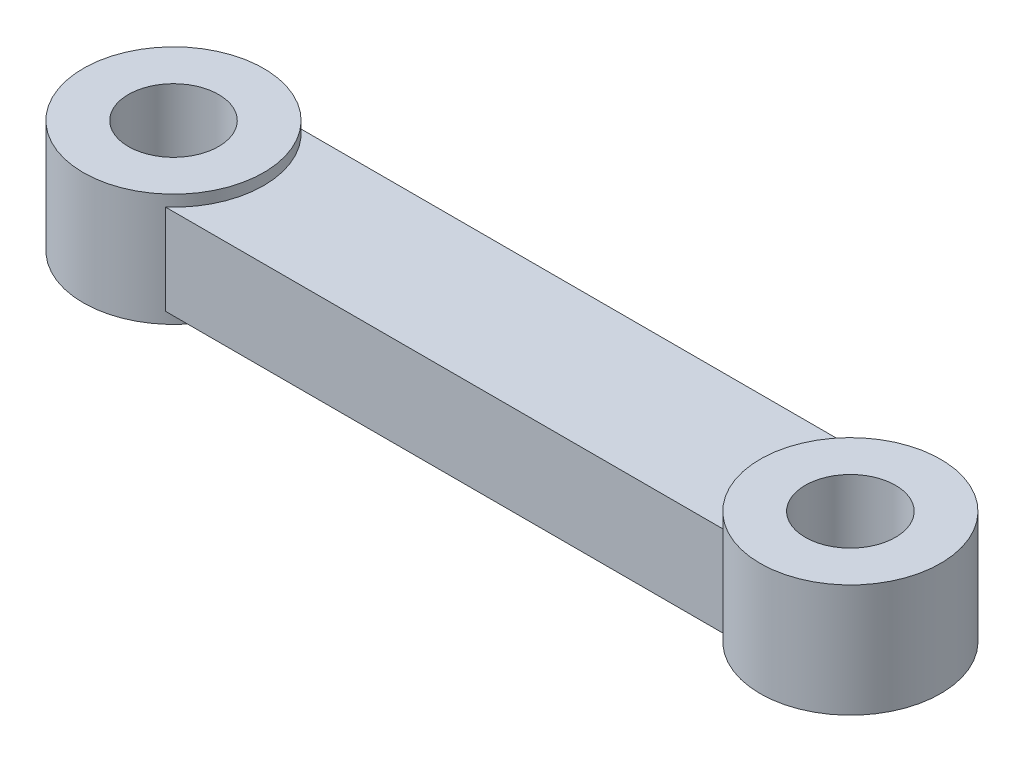
SolidWorks part; units mm, degrees
ref_plane "前视基准面" through (0, 0, 0) normal (0, 0, 1) x (1, 0, 0)
ref_plane "上视基准面" through (0, 0, 0) normal (0, 1, 0) x (1, 0, 0)
ref_plane "右视基准面" through (0, 0, 0) normal (1, 0, 0) x (0, 0, -1)
sketch "草图1" plane through (0, 0, 0) normal (0, 1, 0) x (1, 0, 0)
  circle A1 centre (0, 0) radius 4
  circle A2 centre (0, 0) radius 8
  circle A3 centre (60, 0) radius 8
  circle A4 centre (60, 0) radius 4
  point P7 (0, 0)
  dimension "D1" = 16
  dimension "D2" = 8
  dimension "D3" = 60
extrude "凸台-拉伸1" add sketch "草图1" along normal blind 10
sketch "草图2" plane through (0, 0, 0) normal (0, 1, 0) x (1, 0, 0)
  line L0 (0, 0) -> (60, 0) construction
  line L1 (5.2915, -6) -> (54.7085, -6)
  line L2 (5.2915, 6) -> (54.7085, 6)
  line L4 (0, 6) -> (60, 6) construction
  line L5 (0, -6) -> (60, -6) construction
  circle A0 centre (60, 0) radius 8 construction
  circle A1 centre (0, 0) radius 8 construction
  arc A2 (54.7085, 6) -> (54.7085, -6) centre (60, 0) ccw
  arc A3 (5.2915, -6) -> (5.2915, 6) centre (0, 0) ccw
  dimension "D1" = 6
  dimension "D2" = 6
extrude "凸台-拉伸2" add sketch "草图2" along normal blind 8 from offset 1
